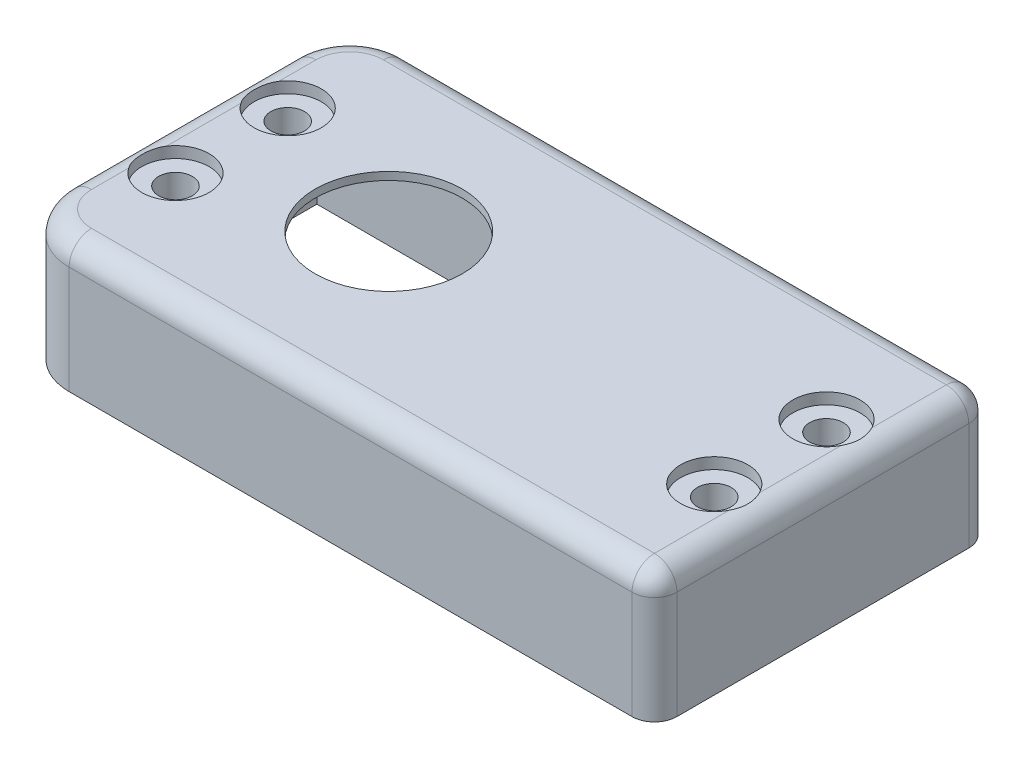
SolidWorks part; units mm, degrees
ref_plane "Front Plane" through (0, 0, 0) normal (0, 0, 1) x (1, 0, 0)
ref_plane "Top Plane" through (0, 0, 0) normal (0, 1, 0) x (1, 0, 0)
ref_plane "Right Plane" through (0, 0, 0) normal (1, 0, 0) x (0, 0, -1)
sketch "Sketch1" plane through (0, 0, 0) normal (0, 1, 0) x (1, 0, 0)
  line L5 (0, 30) -> (57.15, 30)
  line L6 (0, 30) -> (0, 0)
  line L7 (0, 0) -> (57.15, 0)
  line L8 (57.15, 30) -> (57.15, 0)
  dimension "D3" = 57.15
  dimension "D4" = 30
extrude "Boss-Extrude1" add sketch "Sketch1" along normal blind 11.6
sketch "Sketch2" plane through (0, 0, 0) normal (0, -1, 0) x (-1, 0, 0)
  line L0 (-5, 0) -> (-57.15, 0) construction
  line L1 (-1.575, 4.5) -> (-55.575, 4.5)
  line L2 (-1.575, 4.5) -> (-1.575, 25.5)
  line L3 (-1.575, 25.5) -> (-55.575, 25.5)
  line L4 (-55.575, 4.5) -> (-55.575, 25.5)
  line L5 (0, 25) -> (0, 5) construction
  point P4 (-28.575, 0)
  point P7 (-28.575, 4.5)
  point P8 (0, 15)
  point P11 (-1.575, 15)
  dimension "D1" = 54
  dimension "D2" = 21
extrude "Cut-Extrude1" cut sketch "Sketch2" against normal blind 10.9
sketch "Sketch3" plane through (0, 11.6, 0) normal (0, 1, 0) x (1, 0, 0)
  line L1 (0, 30) -> (0, 0) construction
  circle A0 centre (17.58, 15) radius 5.375
  point P5 (0, 15)
  dimension "D1" = 10.75
  dimension "D2" = 17.58
extrude "Cut-Extrude2" cut sketch "Sketch3" against normal blind 0.65 contours A0
fillet "Fillet1" radius 5 2 edges at (0, 5.8, -30) (0, 5.8, 0)
sketch "Sketch5" plane through (0, 10.95, 0) normal (0, 1, 0) x (1, 0, 0)
  circle A0 centre (18.475, 15) radius 6.55
  dimension "D1" = 13.1
extrude "Cut-Extrude3" cut sketch "Sketch5" against normal blind 1.35 and the other way through all
chamfer "Chamfer1" distance 5 angle 60 2 edges at (55.575, 10.9, -15) (1.575, 10.9, -15)
fillet "Fillet2" radius 2 8 edges at (57.15, 11.6, -15) (31.075, 11.6, -30) (1.4645, 11.6, -28.5355) (0, 11.6, -15) (31.075, 11.6, 0) (1.4645, 11.6, -1.4645) (57.15, 5.8, -30) (57.15, 5.8, 0)
sketch "Sketch8" plane through (0, 11.6, 0) normal (0, 1, 0) x (1, 0, 0)
  circle A0 centre (52.475, 20) radius 1.5
  circle A1 centre (52.475, 10) radius 1.5
  circle A2 centre (4.475, 20) radius 1.5
  circle A3 centre (4.475, 10) radius 1.5
  circle A4 centre (18.475, 15) radius 6.55 construction
  dimension "D2" = 3
  dimension "D1" = 48
  dimension "D3" = 10
  dimension "D4" = 14
  dimension "D5" = 5
extrude "Cut-Extrude5" cut sketch "Sketch8" against normal blind 10
sketch "Sketch9" plane through (0, 11.6, 0) normal (0, 1, 0) x (1, 0, 0)
  circle A0 centre (4.475, 20) radius 3
  circle A1 centre (4.475, 10) radius 3
  circle A2 centre (52.475, 10) radius 3
  circle A3 centre (52.475, 20) radius 3
  dimension "D1" = 6
extrude "Cut-Extrude6" cut sketch "Sketch9" against normal blind 1
